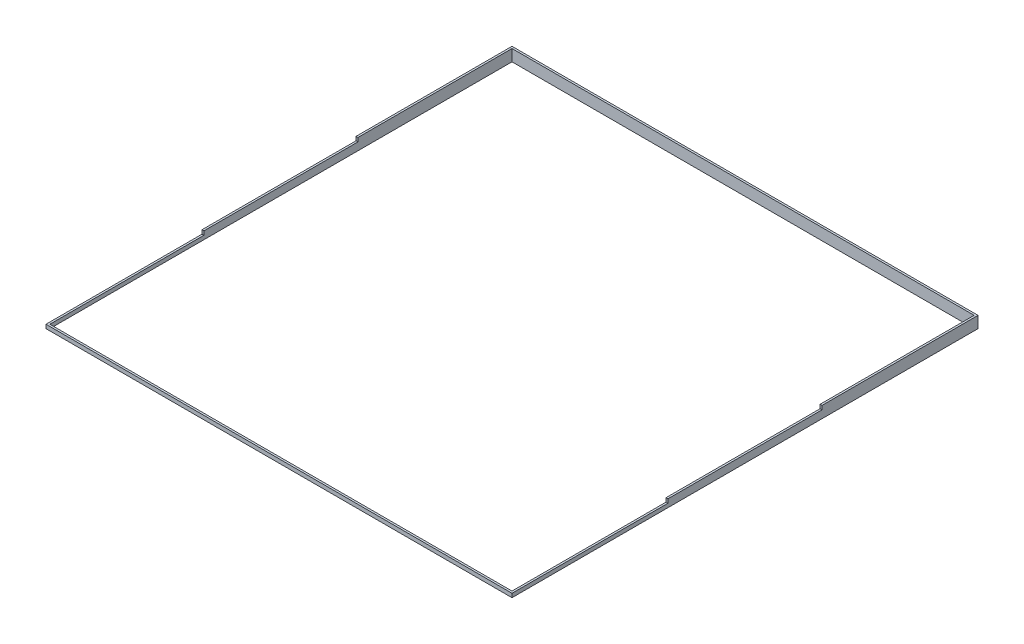
SolidWorks part; units mm, degrees
ref_plane "Front Plane" through (0, 0, 0) normal (0, 0, 1) x (1, 0, 0)
ref_plane "Top Plane" through (0, 0, 0) normal (0, 1, 0) x (1, 0, 0)
ref_plane "Right Plane" through (0, 0, 0) normal (1, 0, 0) x (0, 0, -1)
sketch "Sketch2" plane through (0, 0, 0) normal (0, 1, 0) x (1, 0, 0)
  line L1 (-6050, 6050) -> (6050, 6050)
  line L2 (-6050, 6050) -> (-6050, -6050)
  line L3 (-6050, -6050) -> (6050, -6050)
  line L4 (6050, 6050) -> (6050, -6050)
  line L5 (-6050, 6050) -> (6050, -6050) construction
  line L6 (-6050, -6050) -> (6050, 6050) construction
  point P0 (0, 0)
  dimension "D1" = 12100
  dimension "D2" = 12100
extrude "Boss-Extrude2" add sketch "Sketch2" along normal blind 300 contours L2 L3 L4 L1
sketch "Sketch3" plane through (0, 300, 0) normal (0, 1, 0) x (1, 0, 0)
  line L1 (-6000, 6000) -> (6000, 6000)
  line L2 (-6000, 6000) -> (-6000, -6000)
  line L3 (-6000, -6000) -> (6000, -6000)
  line L4 (6000, 6000) -> (6000, -6000)
  line L5 (-6000, 6000) -> (6000, -6000) construction
  line L6 (-6000, -6000) -> (6000, 6000) construction
  point P0 (0, 0)
  dimension "D1" = 12000
  dimension "D2" = 12000
extrude "Cut-Extrude1" cut sketch "Sketch3" against normal blind 301
sketch "Sketch5" plane through (0, 300, 0) normal (0, 1, 0) x (1, 0, 0)
  line L0 (-6050, 6050) -> (-6050, -6050) construction
  line L1 (-6000, -6000) -> (-6050, -6000)
  line L2 (-6000, -6000) -> (-6000, -2000)
  line L3 (-6000, -2000) -> (-6050, -2000)
  line L4 (-6050, -6000) -> (-6050, -2000)
  dimension "D1" = 4000
extrude "Cut-Extrude2" cut sketch "Sketch5" against normal blind 200
sketch "Sketch6" plane through (0, 300, 0) normal (0, 1, 0) x (1, 0, 0)
  line L0 (-6050, 6050) -> (-6050, -2000) construction
  line L1 (-6000, -2000) -> (-6050, -2000)
  line L2 (-6000, -2000) -> (-6000, 2000)
  line L3 (-6000, 2000) -> (-6050, 2000)
  line L4 (-6050, -2000) -> (-6050, 2000)
  dimension "D1" = 4000
extrude "Cut-Extrude3" cut sketch "Sketch6" against normal blind 100
sketch "Sketch7" plane through (0, 300, 0) normal (0, 1, 0) x (1, 0, 0)
  line L0 (6050, 6050) -> (6050, -6050) construction
  line L1 (6000, -6000) -> (6050, -6000)
  line L2 (6000, -6000) -> (6000, -2000)
  line L3 (6000, -2000) -> (6050, -2000)
  line L4 (6050, -6000) -> (6050, -2000)
  dimension "D1" = 4000
extrude "Cut-Extrude4" cut sketch "Sketch7" against normal blind 200
sketch "Sketch8" plane through (0, 300, 0) normal (0, 1, 0) x (1, 0, 0)
  line L0 (6000, -2000) -> (6000, 6000) construction
  line L1 (6050, -2000) -> (6000, -2000)
  line L2 (6050, -2000) -> (6050, 2000)
  line L3 (6050, 2000) -> (6000, 2000)
  line L4 (6000, -2000) -> (6000, 2000)
  dimension "D1" = 4000
extrude "Cut-Extrude5" cut sketch "Sketch8" against normal blind 100
sketch "Sketch10" plane through (0, 300, 0) normal (0, 1, 0) x (1, 0, 0)
  line L1 (-6050, -6000) -> (6050, -6000)
  line L2 (-6050, -6000) -> (-6050, -6050)
  line L3 (-6050, -6050) -> (6050, -6050)
  line L4 (6050, -6000) -> (6050, -6050)
extrude "Cut-Extrude6" cut sketch "Sketch10" against normal blind 200
